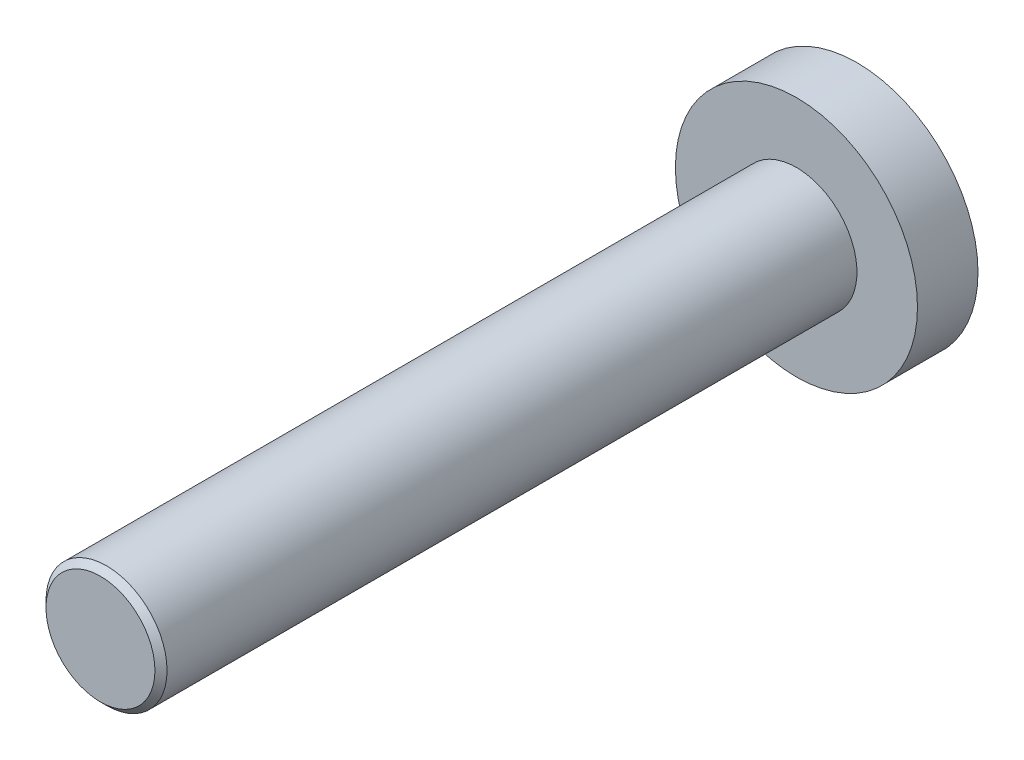
SolidWorks part; units mm, degrees
material "AISI 1020"
ref_plane "前视基准面" through (0, 0, 0) normal (0, 0, 1) x (1, 0, 0)
ref_plane "上视基准面" through (0, 0, 0) normal (0, 1, 0) x (1, 0, 0)
ref_plane "右视基准面" through (0, 0, 0) normal (1, 0, 0) x (0, 0, -1)
sketch "草图1" plane through (0, 0, 0) normal (0, 0, 1) x (1, 0, 0)
  circle A0 centre (0, 0) radius 2
  dimension "D1" = 4
extrude "拉伸1" add sketch "草图1" along normal blind 23
sketch "草图2" plane through (0, 0, 0) normal (0, 0, -1) x (-1, 0, 0)
  circle A0 centre (0, 0) radius 4
  dimension "D1" = 8
extrude "拉伸2" add sketch "草图2" along normal blind 2
chamfer "倒角1" distance 0.2 angle 45 1 edges at (2, 0, 23)
